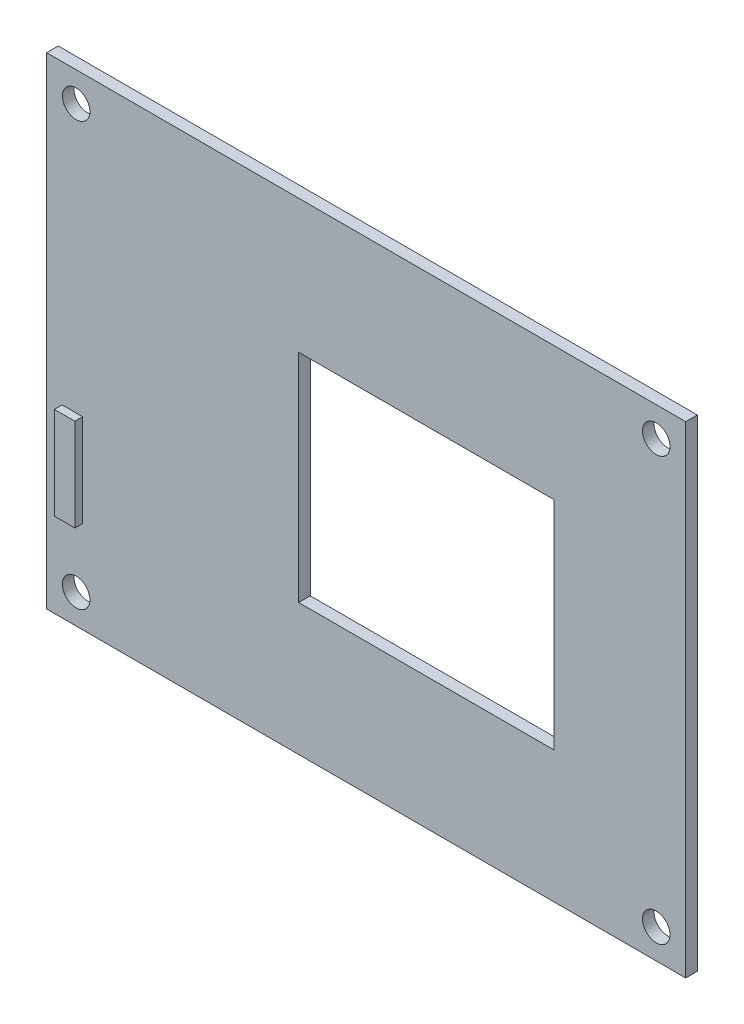
SolidWorks part; units mm, degrees
ref_plane "Front Plane" through (0, 0, 0) normal (0, 0, 1) x (1, 0, 0)
ref_plane "Top Plane" through (0, 0, 0) normal (0, 1, 0) x (1, 0, 0)
ref_plane "Right Plane" through (0, 0, 0) normal (1, 0, 0) x (0, 0, -1)
sketch "Sketch1" plane through (0, 0, 0) normal (0, 0, 1) x (1, 0, 0)
  line L0 (0, 31.115) -> (82.55, 31.115) construction
  line L1 (0, 0) -> (82.55, 0)
  line L2 (0, 0) -> (0, 62.23)
  line L3 (0, 62.23) -> (82.55, 62.23)
  line L4 (82.55, 0) -> (82.55, 62.23)
  line L5 (41.275, 62.23) -> (41.275, 0) construction
  line L6 (3.81, 58.42) -> (3.81, 3.81) construction
  line L7 (3.81, 58.42) -> (78.74, 58.42) construction
  line L9 (32.55, 45) -> (65.55, 45)
  line L10 (32.55, 45) -> (32.55, 17)
  line L11 (32.55, 17) -> (65.55, 17)
  line L12 (65.55, 45) -> (65.55, 17)
  circle A0 centre (3.81, 58.42) radius 1.778
  circle A1 centre (78.74, 58.42) radius 1.778
  circle A2 centre (78.74, 3.81) radius 1.778
  circle A3 centre (3.81, 3.81) radius 1.778
  point P14 (41.275, 58.42)
  point P15 (3.81, 31.115)
  point P16 (0, 0)
  dimension "D5" = 3.556
  dimension "D1" = 82.55
  dimension "D2" = 62.23
  dimension "D3" = 54.61
  dimension "D4" = 74.93
  dimension "D6" = 17
  dimension "D7" = 33
  dimension "D8" = 28
  dimension "D9" = 17
extrude "Boss-Extrude1" add sketch "Sketch1" along normal blind 1.5
sketch "Sketch2" plane through (0, 0, 1.5) normal (0, 0, 1) x (1, 0, 0)
  line L0 (0, 62.23) -> (0, 0) construction
  line L1 (2, 23.8303) -> (4.6428, 23.8303)
  line L2 (2, 23.8303) -> (2, 11.8849)
  line L3 (2, 11.8849) -> (4.6428, 11.8849)
  line L4 (4.6428, 23.8303) -> (4.6428, 11.8849)
  dimension "D1" = 2
extrude "Boss-Extrude2" add sketch "Sketch2" along normal blind 1
sketch "Sketch3" plane through (0, 0, 0) normal (0, 0, -1) x (-1, 0, 0)
  line L0 (0, 62.23) -> (0, 0) construction
  line L1 (-4, 37.7423) -> (-11.0437, 37.7423)
  line L2 (-4, 37.7423) -> (-4, 27.3396)
  line L3 (-4, 27.3396) -> (-11.0437, 27.3396)
  line L4 (-11.0437, 37.7423) -> (-11.0437, 27.3396)
  dimension "D1" = 4
extrude "Boss-Extrude3" add sketch "Sketch3" along normal blind 2
